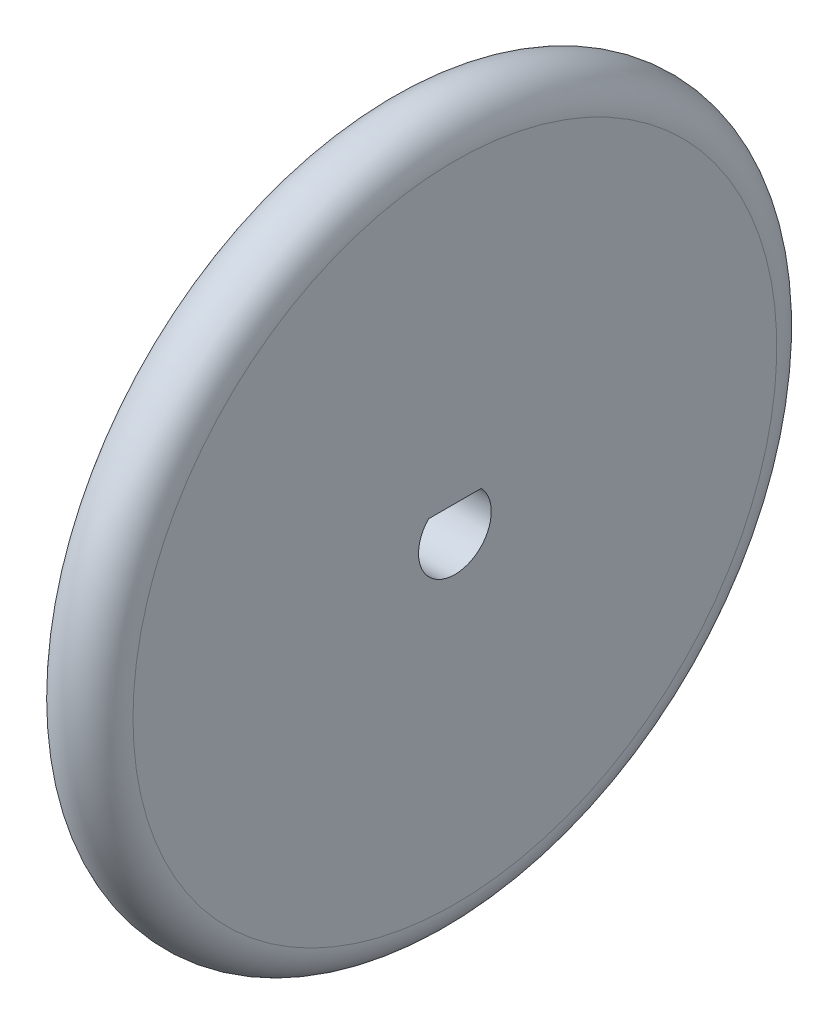
SolidWorks part; units mm, degrees
ref_plane "正面" through (0, 0, 0) normal (0, 0, 1) x (1, 0, 0)
ref_plane "平面" through (0, 0, 0) normal (0, 1, 0) x (1, 0, 0)
ref_plane "右側面" through (0, 0, 0) normal (1, 0, 0) x (0, 0, -1)
sketch "ｽｹｯﾁ2" plane through (0, 0, 0) normal (0, 0, 1) x (1, 0, 0)
  line L0 (-1.5, 13.5) -> (-1.5, 0)
  line L1 (-1.5, 0) -> (1.5, 0)
  line L2 (1.5, 0) -> (1.5, 13.5)
  line L3 (0, 0) -> (0, 15) construction
  line L4 (0, 0) -> (18.3643, 0) construction
  arc A0 (1.5, 13.5) -> (-1.5, 13.5) centre (0, 13.5) ccw
  dimension "D1" = 15
  dimension "D2" = 3
revolve "回転1" add sketch "ｽｹｯﾁ2" angle 360 about L4
sketch "ｽｹｯﾁ3" plane through (-1.5, 0, 0) normal (-1, 0, 0) x (0, 0, 1)
  circle A0 centre (0, 0) radius 4
  dimension "D1" = 8
extrude "ﾎﾞｽ - 押し出し1" add sketch "ｽｹｯﾁ3" along normal blind 3
sketch "ｽｹｯﾁ4" plane through (-4.5, 0, 0) normal (-1, 0, 0) x (0, 0, 1)
  line L0 (-1.1059, 1.05) -> (1.1059, 1.05)
  arc A0 (-1.1059, 1.05) -> (1.1059, 1.05) centre (0, 0) ccw
  dimension "D1" = 3.05
  dimension "D2" = 1.05
extrude "ｶｯﾄ - 押し出し1" cut sketch "ｽｹｯﾁ4" against normal through all
ref_plane "平面1" through (0, 0, 15) normal (0, 0, 1) x (1, 0, 0)
